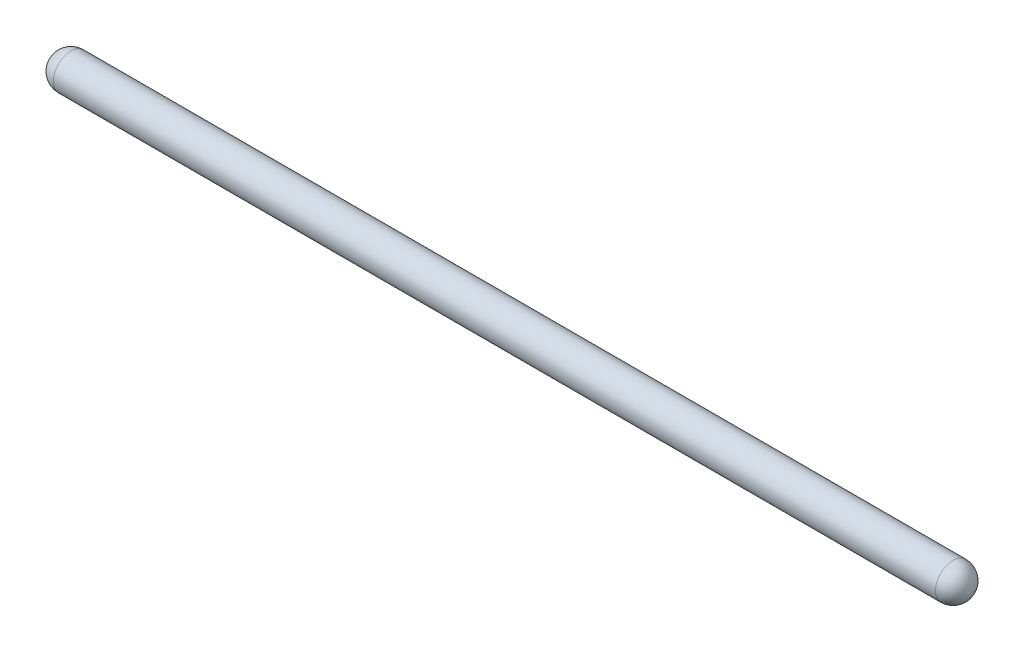
SolidWorks part; units mm, degrees
material "Stainless Steel (ferritic)"
ref_plane "Front Plane" through (0, 0, 0) normal (0, 0, 1) x (1, 0, 0)
ref_plane "Top Plane" through (0, 0, 0) normal (0, 1, 0) x (1, 0, 0)
ref_plane "Right Plane" through (0, 0, 0) normal (1, 0, 0) x (0, 0, -1)
sketch "Sketch1" plane through (0, 0, 0) normal (1, 0, 0) x (0, 0, -1)
  circle A0 centre (0, 0) radius 0.7937
  dimension "D1" = 1.5875
extrude "Boss-Extrude1" add sketch "Sketch1" along normal blind 41.275
fillet "Fillet1" radius 0.7937 2 edges at (41.275, 0, -0.7937) (0, 0, -0.7937)
